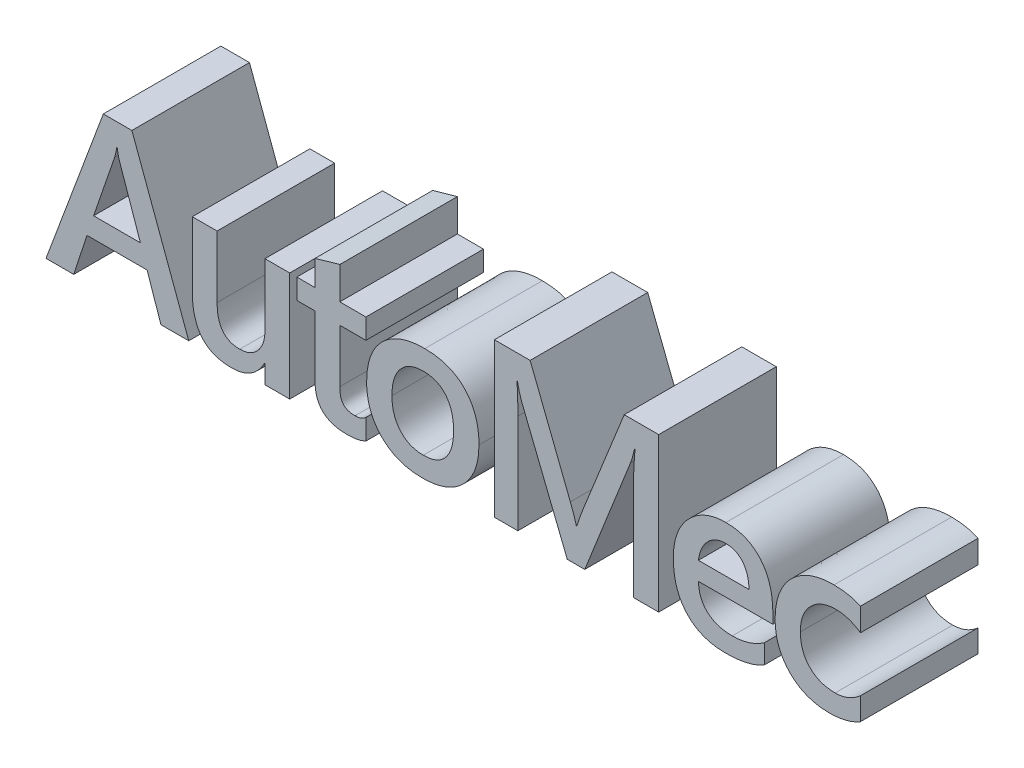
SolidWorks part; units mm, degrees
ref_plane "Front Plane" through (0, 0, 0) normal (0, 0, 1) x (1, 0, 0)
ref_plane "Top Plane" through (0, 0, 0) normal (0, 1, 0) x (1, 0, 0)
ref_plane "Right Plane" through (0, 0, 0) normal (1, 0, 0) x (0, 0, -1)
sketch "Sketch1" plane through (0, 0, 0) normal (0, 0, 1) x (1, 0, 0)
  text T0 "AutoMec" font "@Yu Gothic UI" height 34
extrude "Boss-Extrude1" add sketch "Sketch1" along normal blind 26
